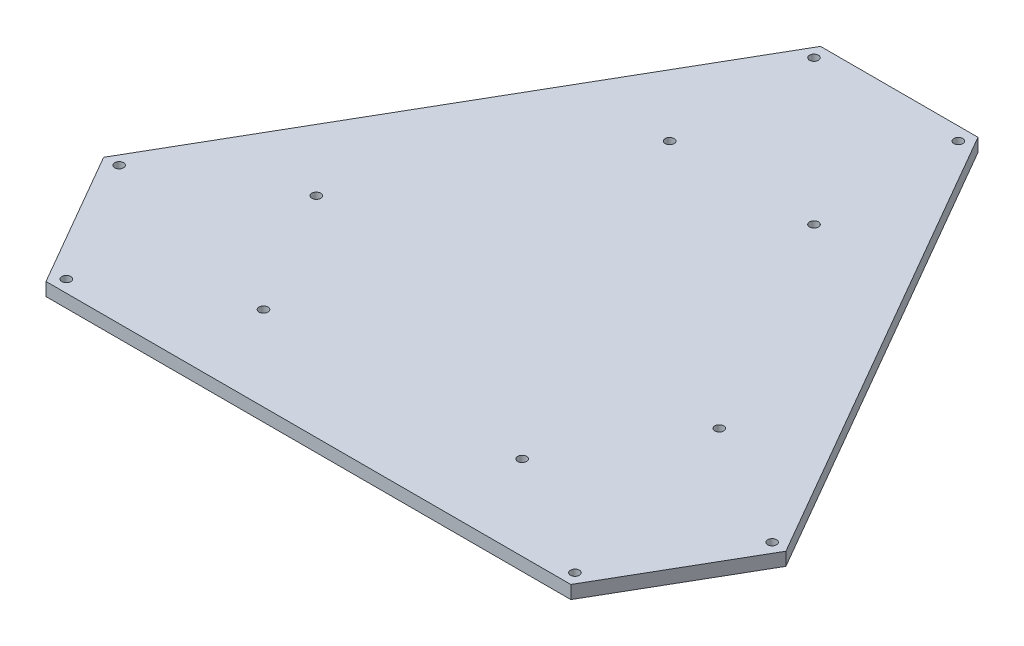
SolidWorks part; units mm, degrees
ref_plane "Front Plane" through (0, 0, 0) normal (0, 0, 1) x (1, 0, 0)
ref_plane "Top Plane" through (0, 0, 0) normal (0, 1, 0) x (1, 0, 0)
ref_plane "Right Plane" through (0, 0, 0) normal (1, 0, 0) x (0, 0, -1)
sketch "Sketch1" plane through (0, 0, 0) normal (0, 1, 0) x (1, 0, 0)
  line L0 (-30, 132.7906) -> (30, 132.7906)
  line L1 (30, 132.7906) -> (130, -40.4145)
  line L2 (130, -40.4145) -> (100, -92.376)
  line L3 (100, -92.376) -> (-100, -92.376)
  line L4 (-100, -92.376) -> (-130, -40.4145)
  line L5 (-130, -40.4145) -> (-30, 132.7906)
  line L6 (-80, 46.188) -> (115, -66.3953) construction
  line L7 (-115, -66.3953) -> (80, 46.188) construction
  line L8 (0, 132.7906) -> (0, -92.376) construction
  circle A0 centre (-27.5, 127.7906) radius 1.7
  circle A1 centre (-27.5, 72.7906) radius 1.7
  circle A2 centre (27.5, 127.7906) radius 1.7
  circle A3 centre (27.5, 72.7906) radius 1.7
  circle A4 centre (76.7885, -12.5796) radius 1.7
  circle A5 centre (49.2885, -60.211) radius 1.7
  circle A6 centre (96.9199, -87.711) radius 1.7
  circle A7 centre (124.4199, -40.0796) radius 1.7
  circle A8 centre (-49.2885, -60.211) radius 1.7
  circle A9 centre (-76.7885, -12.5796) radius 1.7
  circle A10 centre (-124.4199, -40.0796) radius 1.7
  circle A11 centre (-96.9199, -87.711) radius 1.7
  point P13 (0, 0)
  point P42 (0, 0)
  dimension "D2" = 200
  dimension "D5" = 3.4
  dimension "D1" = 60
  dimension "D3" = 55
  dimension "D4" = 55
  dimension "D6" = 5
  dimension "D7" = 3
extrude "Boss-Extrude1" add sketch "Sketch1" along normal blind 5
